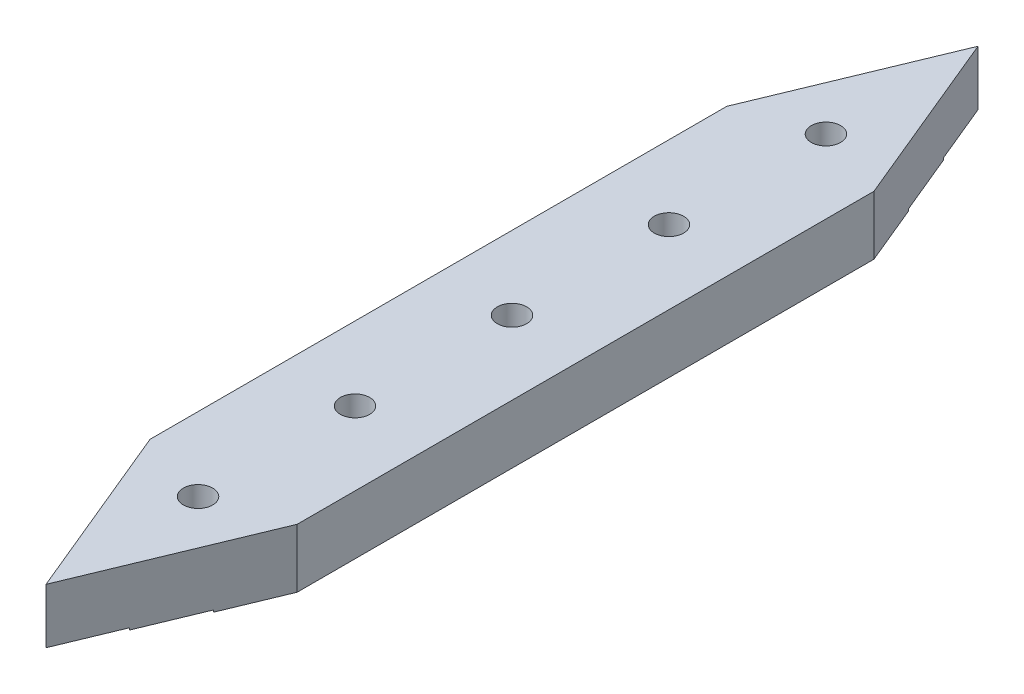
SolidWorks part; units mm, degrees
material "6061 Alloy"
ref_plane "Front Plane" through (0, 0, 0) normal (0, 0, 1) x (1, 0, 0)
ref_plane "Top Plane" through (0, 0, 0) normal (0, 1, 0) x (1, 0, 0)
ref_plane "Right Plane" through (0, 0, 0) normal (1, 0, 0) x (0, 0, -1)
sketch "Sketch1" plane through (0, 0, 0) normal (0, 1, 0) x (1, 0, 0)
  line L0 (0, 60.325) -> (0, -48.1572) construction
  line L1 (0, 60.325) -> (-9.525, 37.3296)
  line L2 (-9.525, 37.3296) -> (-9.525, -37.3296)
  line L3 (-28.5797, 0) -> (23.9031, 0) construction
  line L4 (0, -60.325) -> (-9.525, -37.3296)
  line L5 (0, -60.325) -> (9.525, -37.3296)
  line L6 (9.525, 37.3296) -> (9.525, -37.3296)
  line L7 (0, 60.325) -> (9.525, 37.3296)
  point P9 (-9.525, 0)
  point P10 (9.525, 0)
  dimension "D1" = 19.05
  dimension "D2" = 120.65
  dimension "D3" = 22.5
extrude "Boss-Extrude1" add sketch "Sketch1" along normal blind 7.62
sketch "Sketch2" plane through (0, 0, 0) normal (0, -1, 0) x (1, 0, 0)
  line L0 (0, 60.325) -> (0, -60.325) construction
  line L1 (6.35, 60.325) -> (-6.35, 60.325)
  line L2 (-6.35, 60.325) -> (-6.35, -60.325)
  line L3 (-6.35, -60.325) -> (6.35, -60.325)
  line L4 (6.35, 60.325) -> (6.35, -60.325)
  dimension "D1" = 12.7
extrude "Cut-Extrude1" cut sketch "Sketch2" against normal blind 0.254
sketch "Sketch3" plane through (0, 0.254, 0) normal (0, -1, 0) x (1, 0, 0)
  line L0 (0, 60.325) -> (0, -60.325) construction
  line L1 (3.175, 60.325) -> (-3.175, 60.325)
  line L2 (-3.175, 60.325) -> (-3.175, -60.325)
  line L3 (-3.175, -60.325) -> (3.175, -60.325)
  line L4 (3.175, 60.325) -> (3.175, -60.325)
  dimension "D1" = 6.35
extrude "Cut-Extrude2" cut sketch "Sketch3" against normal blind 0.254
hole_wizard "#10-24 Tapped Hole1" positions "Sketch4" profile "Sketch5" tap size "#10-24" standard "ANSI Inch" end condition through all
sketch "Sketch4" plane through (0, 7.62, 0) normal (0, 1, 0) x (1, 0, 0)
  line L0 (-9.525, 0) -> (9.525, 0) construction
  line L1 (-9.525, 37.3296) -> (-9.525, -37.3296) construction
  line L2 (9.525, -37.3296) -> (9.525, 37.3296) construction
  point P0 (0, 20.32)
  point P2 (0, 40.64)
  point P14 (0, 0)
  point P16 (0, -20.32)
  point P18 (0, -40.64)
  dimension "D1" = 20.32
  dimension "D2" = 40.64
  dimension "D3" = 20.32
  dimension "D4" = 40.64
cosmetic thread "Hole Thread1" parameters "D2"=4.826
cosmetic thread "Hole Thread2" parameters "D2"=4.826
cosmetic thread "Hole Thread3" parameters "D2"=4.826
cosmetic thread "Hole Thread4" parameters "D2"=4.826
cosmetic thread "Hole Thread5" parameters "D2"=4.826
sketch "Sketch5" plane through (0, 7.62, -20.32) normal (1, 0, 0) x (0, 0, 1)
  line L0 (0, 0) -> (0, 7.62)
  line L1 (0, 7.62) -> (1.8986, 7.62)
  line L2 (1.8986, 7.62) -> (1.8986, 0)
  line L5 (1.8986, 0) -> (0, 0)
  line L11 (0, -6.35) -> (0, 107.95) construction
  dimension "Thru Tap Drill Dia." = 3.7973
  dimension "Thru Tap Drill Depth" = 7.62
